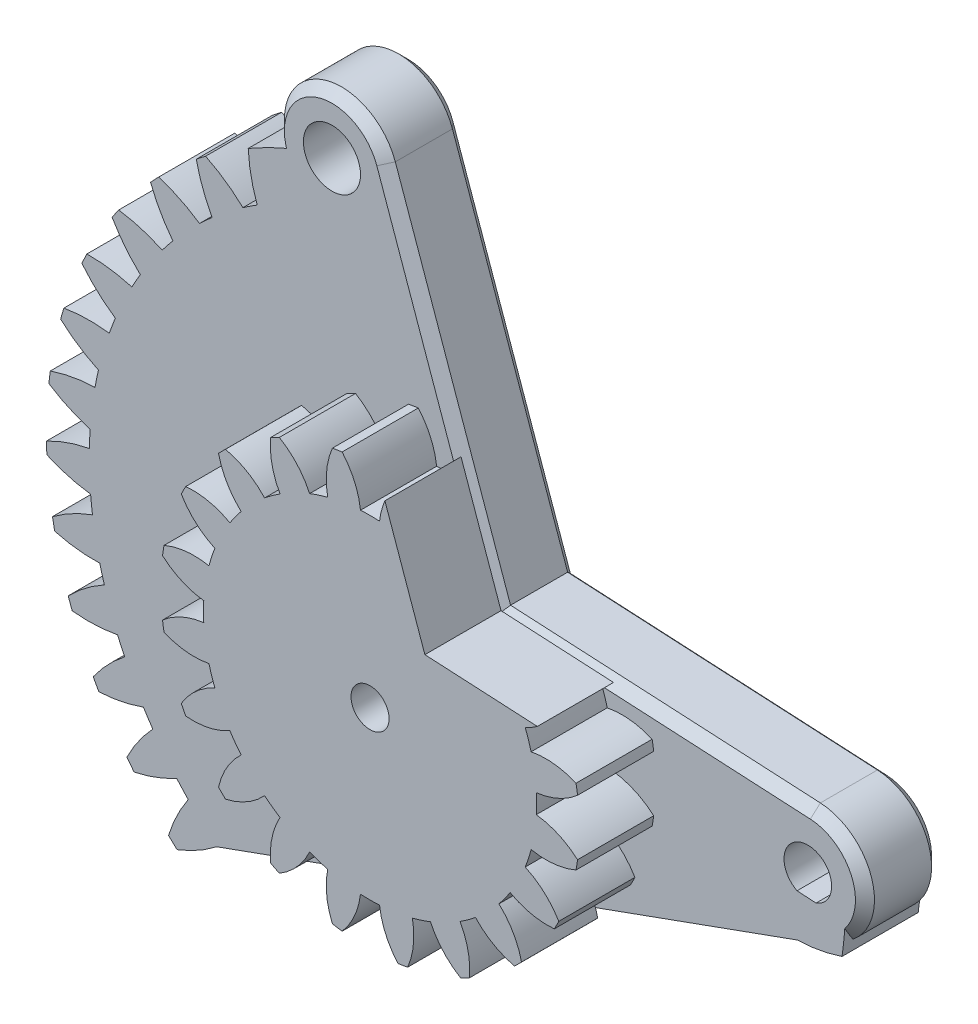
SolidWorks part; units mm, degrees
ref_plane "Alzado" through (0, 0, 0) normal (0, 0, 1) x (1, 0, 0)
ref_plane "Planta" through (0, 0, 0) normal (0, 1, 0) x (1, 0, 0)
ref_plane "Vista lateral" through (0, 0, 0) normal (1, 0, 0) x (0, 0, -1)
sketch "Croquis1" plane through (0, 0, 0) normal (0, 0, 1) x (1, 0, 0)
  line L0 (0, 0) -> (16185.8284, 0) construction
  line L1 (0, 0) -> (19, 0) construction
  line L2 (0.2105, 3.9945) -> (19.1579, 2.9958)
  line L3 (0.2105, -3.9945) -> (19.1579, -2.9958)
  circle A0 centre (0, 0) radius 1
  circle A1 centre (19, 0) radius 1.25
  arc A3 (19.1579, -2.9958) -> (19.1579, 2.9958) centre (19, 0) ccw
  arc A4 (0.2105, 3.9945) -> (0.2105, -3.9945) centre (0, 0) ccw
  point P5 (9.5, 0)
  dimension "D2" = 3
  dimension "D3" = 2.5
  dimension "D4" = 2
  dimension "D5" = 8
  dimension "D1" = 19
extrude "Saliente-Extruir1" add sketch "Croquis1" along normal blind 4
sketch "Croquis2" plane through (0, 0, 4) normal (0, 0, 1) x (1, 0, 0)
  line L6 (-3.1711, 20.9987) -> (3.7719, 1.3316)
  line L7 (-8.9115, 19.2766) -> (-3.882, -0.9646)
  circle A1 centre (0, 0) radius 1
  circle A2 centre (-6, 20) radius 1.5
  arc A3 (-3.1711, 20.9987) -> (-8.9115, 19.2766) centre (-6, 20) ccw
  arc A4 (-3.882, -0.9646) -> (3.7719, 1.3316) centre (0, 0) ccw
  dimension "D1" = 3
  dimension "D2" = 3
  dimension "D3" = 20
  dimension "D4" = 6
extrude "Saliente-Extruir2" add sketch "Croquis2" against normal through all
chamfer "Chaflán1" distance 0.5 angle 45 14 edges at (9.6842, -3.4951, 0) (9.6842, -3.4951, 4) (22, 0, 0) (22, 0, 4) (11.0197, 3.4248, 0) (11.0197, 3.4248, 4) (-2.3801, -3.2148, 4) (-2.3801, -3.2148, 0) (-0.1448, 12.4262, 0) (-6.862, 22.8735, 0) (-6.3967, 9.156, 0) (-0.1448, 12.4262, 4) (-6.862, 22.8735, 4) (-6.3967, 9.156, 4)
sketch "Croquis5" plane through (0, 0, 4) normal (0, 0, 1) x (1, 0, 0)
  line L0 (-8.1254, 19.3643) -> (-0.3869, 0.9221)
  line L1 (0.9982, -0.0603) -> (20.9618, -1.2661)
  arc A0 (20.9618, -1.2661) -> (-8.1254, 19.3643) centre (0, 0) cw
  arc A1 (-0.3869, 0.9221) -> (0.9982, -0.0603) centre (0, 0) ccw
  dimension "D1" = 21
extrude "Saliente-Extruir3" add sketch "Croquis5" against normal through all
sketch "Croquis4" plane through (0, 0, 0) normal (0, 0, 1) x (1, 0, 0)
  line L1 (0, 0) -> (-58.6438, 89.1281) construction
  line L2 (0, 0) -> (-11.6947, 16.2245) construction
  line L3 (0, 0) -> (-24.5246, 31.5671) construction
  line L4 (-11.6947, 16.2245) -> (-12.2623, 15.7835) construction
  arc A0 (-9.9278, 15.9048) -> (-10.6775, 15.4116) centre (0, 0) ccw
  arc A1 (-10.4011, 18.2725) -> (-12.6646, 16.7832) centre (0, 0) ccw
  circle A2 centre (0, 0) radius 20 construction
  circle A3 centre (0, 0) radius 18.7939 construction
  arc A4 (-10.6775, 15.4116) -> (-12.6646, 16.7832) centre (-16.1636, 9.589) ccw
  arc A5 (-10.4011, 18.2725) -> (-9.9278, 15.9048) centre (-2.4095, 18.6388) ccw
  dimension "Root_dia" = 37.498
  dimension "Overcut_dia" = 42.0508
  dimension "Pitch_dia" = 40
  dimension "Base_dia" = 37.5877
  dimension "Flank_rad" = 8
  dimension "Half_ang" = 4.5
  dimension "Half_CT" = 0.7187
extrude "Cortar-Extruir1" cut sketch "Croquis4" along normal blind 10
pattern_circular "MatrizC1" count 26 every 9 about axis through (0, 0, 0) along (0, 0, 1) of "Cortar-Extruir1"
sketch "Croquis9" plane through (0, 0, 4) normal (0, 0, 1) x (1, 0, 0)
  line L0 (-12.0585, -14.3568) -> (18.4477, -3.3475)
  line L1 (18.4477, -3.3475) -> (41.7926, -9.999)
  line L2 (41.7926, -9.999) -> (3.3305, -34.9293)
  line L3 (3.3305, -34.9293) -> (-27.1251, -28.4282)
  line L4 (-27.1251, -28.4282) -> (-12.0585, -14.3568)
extrude "Cortar-Extruir3" cut sketch "Croquis9" against normal blind 10
sketch "Croquis7" plane through (0, 0, 4) normal (0, 0, 1) x (1, 0, 0)
  circle A0 centre (0, 0) radius 11
  circle A1 centre (0, 0) radius 1
  dimension "D1" = 22
extrude "Saliente-Extruir4" add sketch "Croquis7" along normal blind 4
sketch "Croquis8" plane through (0, 0, 8) normal (0, 0, 1) x (1, 0, 0)
  line L1 (0, 0) -> (0, 107) construction
  line L2 (0, 0) -> (-0.8511, 9.9637) construction
  line L3 (0, 0) -> (-3.1206, 19.7028) construction
  line L4 (-0.8511, 9.9637) -> (-1.5603, 9.8514) construction
  arc A0 (0.4999, 8.7347) -> (-0.4999, 8.7347) centre (0, 0) ccw
  arc A1 (1.4852, 10.9249) -> (-1.4852, 10.9249) centre (0, 0) ccw
  circle A2 centre (0, 0) radius 10 construction
  circle A3 centre (0, 0) radius 9.3969 construction
  arc A4 (-0.4999, 8.7347) -> (-1.4852, 10.9249) centre (-4.4722, 8.2645) ccw
  arc A5 (1.4852, 10.9249) -> (0.4999, 8.7347) centre (4.4722, 8.2645) ccw
  dimension "Root_dia" = 17.498
  dimension "Overcut_dia" = 22.0508
  dimension "Pitch_dia" = 20
  dimension "Base_dia" = 18.7939
  dimension "Flank_rad" = 4
  dimension "Half_ang" = 9
  dimension "Half_CT" = 0.7181
extrude "Cortar-Extruir2" cut sketch "Croquis8" against normal blind 4
pattern_circular "MatrizC2" count 20 over 360 about axis through (0, 0, 0) along (0, 0, 1) of "Cortar-Extruir2"
sketch "Croquis10" plane through (0, 0, 8) normal (0, 0, 1) x (1, 0, 0)
  line L0 (-3.1711, 20.9987) -> (2.8815, 3.8537)
  line L1 (2.8815, 3.8537) -> (19.1579, 2.9958) construction
  line L2 (-3.1711, 20.9987) -> (2.8815, 3.8537) construction
  line L3 (2.8815, 3.8537) -> (19.1579, 2.9958)
  line L4 (19.1579, 2.9958) -> (14.4803, 14.8756)
  line L5 (14.4803, 14.8756) -> (-3.1711, 20.9987)
extrude "Cortar-Extruir4" cut sketch "Croquis10" against normal through all
